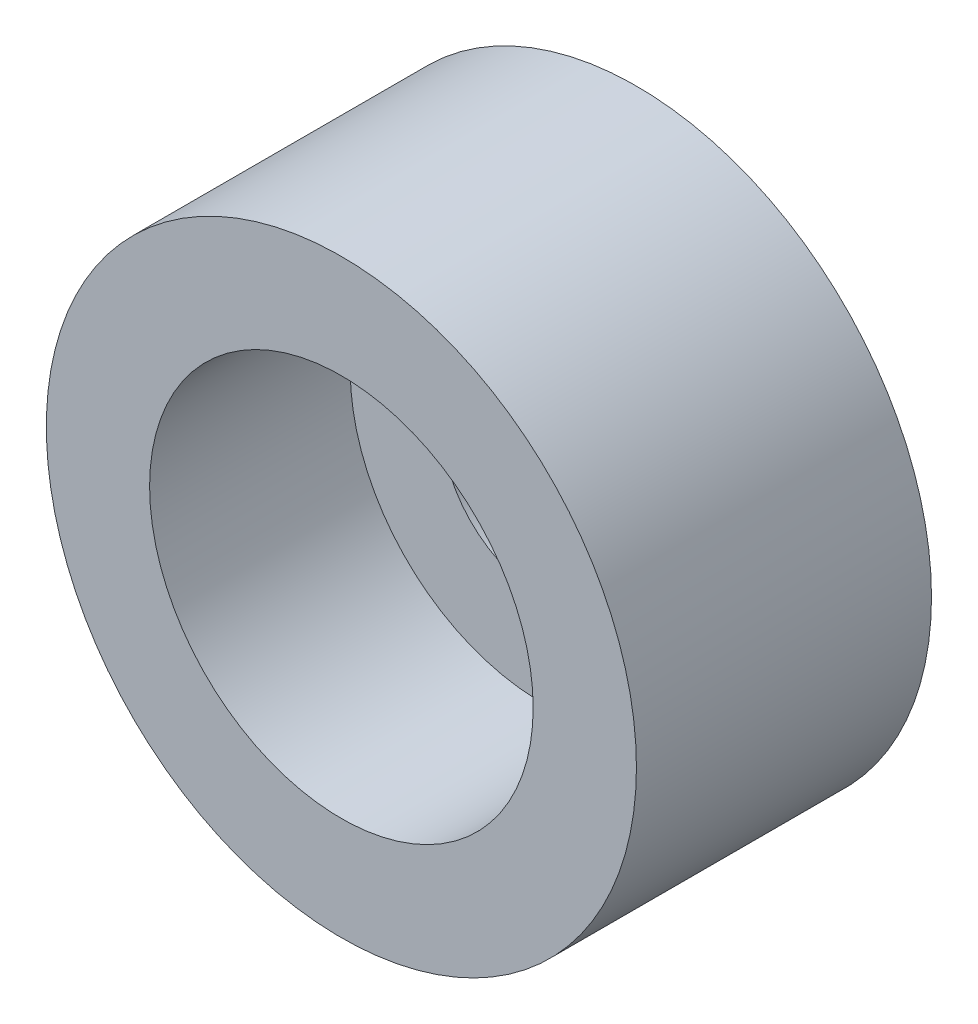
SolidWorks part; units mm, degrees
ref_plane "Front Plane" through (0, 0, 0) normal (0, 0, 1) x (1, 0, 0)
ref_plane "Top Plane" through (0, 0, 0) normal (0, 1, 0) x (1, 0, 0)
ref_plane "Right Plane" through (0, 0, 0) normal (1, 0, 0) x (0, 0, -1)
sketch "Sketch1" plane through (0, 0, 0) normal (0, 0, 1) x (1, 0, 0)
  circle A0 centre (0, 0) radius 5
  dimension "D1" = 10
extrude "Boss-Extrude1" add sketch "Sketch1" along normal blind 5
sketch "Sketch2" plane through (0, 0, 5) normal (0, 0, 1) x (1, 0, 0)
  point P0 (0, 0)
hole_wizard "CBORE for M3 Socket Head Cap Screw1" positions "3DSketch3" profile "Sketch3" counterbore size "M3" standard "DIN" end condition through all
sketch3d "3DSketch3"
  point P0 (0, 0, 5)
sketch "Sketch3" plane through (0, 0, 5) normal (1, 0, 0) x (0, -1, 0)
  line L0 (0, 0) -> (0, 5)
  line L1 (0, 5) -> (1.7, 5)
  line L3 (1.7, 5) -> (1.7, 3.4)
  line L4 (1.7, 3.4) -> (3.25, 3.4)
  line L5 (3.25, 3.4) -> (3.25, 0)
  line L7 (3.25, 0) -> (0, 0)
  line L11 (0, -6.35) -> (0, 107.95) construction
  dimension "Thru Hole Dia." = 3.4
  dimension "Thru Hole Depth" = 5
  dimension "C'Bore Dia." = 6.5
  dimension "C'Bore Depth" = 3.4
